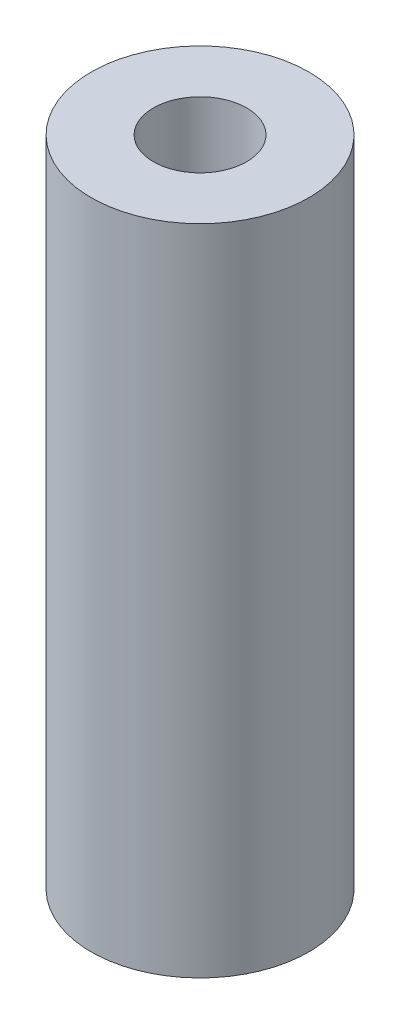
SolidWorks part; units mm, degrees
ref_plane "Front Plane" through (0, 0, 0) normal (0, 0, 1) x (1, 0, 0)
ref_plane "Top Plane" through (0, 0, 0) normal (0, 1, 0) x (1, 0, 0)
ref_plane "Right Plane" through (0, 0, 0) normal (1, 0, 0) x (0, 0, -1)
sketch "Sketch1" plane through (0, 0, 0) normal (0, 1, 0) x (1, 0, 0)
  circle A0 centre (0, 0) radius 3.5
  circle A1 centre (0, 0) radius 1.5
  dimension "D1" = 3
  dimension "D2" = 7
extrude "Boss-Extrude1" add sketch "Sketch1" along normal blind 21
